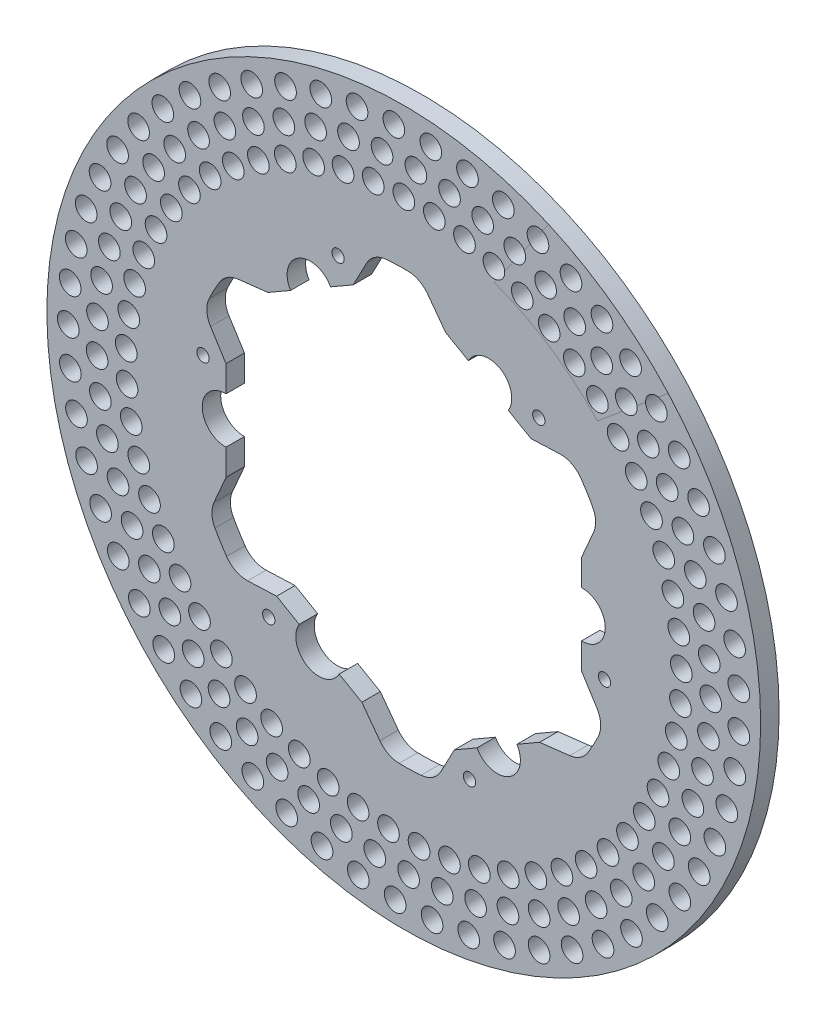
SolidWorks part; units mm, degrees
material "Gray Cast Iron"
ref_plane "Front Plane" through (0, 0, 0) normal (0, 0, 1) x (1, 0, 0)
ref_plane "Top Plane" through (0, 0, 0) normal (0, 1, 0) x (1, 0, 0)
ref_plane "Right Plane" through (0, 0, 0) normal (1, 0, 0) x (0, 0, -1)
sketch "Sketch1" plane through (0, 0, 0) normal (0, 0, 1) x (1, 0, 0)
  line L0 (-55.5625, 0) -> (-55.5625, -25.0191) construction
  line L1 (-45.8597, 11.4094) -> (-45.8597, 4.6599)
  line L2 (-45.8597, 11.4094) -> (-51.6236, 20.5474)
  line L3 (-45.8597, -13.9906) -> (-50.1583, -23.9026)
  line L4 (-45.8597, -7.2411) -> (-45.8597, -13.9906)
  line L5 (-13.049, 45.4204) -> (-8.0172, 54.981)
  line L6 (-13.049, 45.4204) -> (-18.8943, 42.0456)
  line L7 (-29.2008, 36.0951) -> (-35.0461, 32.7204)
  line L8 (-35.0461, 32.7204) -> (-45.7794, 31.4871)
  line L9 (32.8107, 34.011) -> (43.6064, 34.4336)
  line L10 (32.8107, 34.011) -> (26.9654, 37.3857)
  line L11 (16.6589, 43.3362) -> (10.8136, 46.711)
  line L12 (10.8136, 46.711) -> (4.3789, 55.3897)
  line L13 (45.8597, -11.4094) -> (51.6236, -20.5474)
  line L14 (45.8597, -11.4094) -> (45.8597, -4.6599)
  line L15 (45.8597, 7.2411) -> (45.8597, 13.9906)
  line L16 (45.8597, 13.9906) -> (50.1583, 23.9026)
  line L17 (13.049, -45.4204) -> (8.0172, -54.981)
  line L18 (13.049, -45.4204) -> (18.8943, -42.0456)
  line L19 (29.2008, -36.0951) -> (35.0461, -32.7204)
  line L20 (35.0461, -32.7204) -> (45.7794, -31.4871)
  line L21 (-32.8107, -34.011) -> (-43.6064, -34.4336)
  line L22 (-32.8107, -34.011) -> (-26.9654, -37.3857)
  line L23 (-16.6589, -43.3362) -> (-10.8136, -46.711)
  line L24 (-10.8136, -46.711) -> (-4.3789, -55.3897)
  circle A0 centre (0, 0) radius 92.075
  arc A1 (-45.7794, 31.4871) -> (-51.6236, 20.5474) centre (0, 0) ccw
  arc A3 (-45.8597, 4.6599) -> (-45.8597, -7.2411) centre (-46.0375, -1.2906) ccw
  arc A4 (-18.8943, 42.0456) -> (-29.2008, 36.0951) centre (-24.1364, 39.2243) ccw
  arc A5 (26.9654, 37.3857) -> (16.6589, 43.3362) centre (21.9011, 40.5149) ccw
  arc A6 (45.8597, -4.6599) -> (45.8597, 7.2411) centre (46.0375, 1.2906) ccw
  arc A7 (18.8943, -42.0456) -> (29.2008, -36.0951) centre (24.1364, -39.2243) ccw
  arc A8 (-26.9654, -37.3857) -> (-16.6589, -43.3362) centre (-21.9011, -40.5149) ccw
  arc A9 (4.3789, 55.3897) -> (-8.0172, 54.981) centre (0, 0) ccw
  arc A10 (50.1583, 23.9026) -> (43.6064, 34.4336) centre (0, 0) ccw
  arc A11 (45.7794, -31.4871) -> (51.6236, -20.5474) centre (0, 0) ccw
  arc A12 (-4.3789, -55.3897) -> (8.0172, -54.981) centre (0, 0) ccw
  arc A13 (-55.5625, 0) -> (-43.6064, -34.4336) centre (0, 0) ccw
  point P4 (0, 0)
  point P50 (0, 0)
  dimension "D1" = 184.15
  dimension "D2" = 111.125
  dimension "D3" = 11.9062
  dimension "D4" = 9.525
  dimension "D5" = 0.1778
  dimension "D6" = 25.4
  dimension "D7" = 44.45
  dimension "D9" = 47.2577
  dimension "D8" = 6
extrude "Boss-Extrude1" add sketch "Sketch1" along normal blind 4.7625
fillet "Fillet1" radius 6.35 12 edges at (8.0172, -54.981, 2.3813) (45.7794, -31.4871, 2.3813) (-4.3789, -55.3897, 2.3813) (-43.6064, -34.4336, 2.3813) (51.6236, -20.5474, 2.3813) (50.1583, 23.9026, 2.3813) (43.6064, 34.4336, 2.3813) (4.3789, 55.3897, 2.3813) (-50.1583, -23.9026, 2.3813) (-51.6236, 20.5474, 2.3813) (-8.0172, 54.981, 2.3813) (-45.7794, 31.4871, 2.3813)
sketch "Sketch4" plane through (0, 0, 4.7625) normal (0, 0, 1) x (1, 0, 0)
  circle A0 centre (-16.953, 50.0113) radius 1.5875
  arc A1 (-18.8943, 42.0456) -> (-29.2008, 36.0951) centre (-24.1364, 39.2243) ccw construction
  circle A3 centre (34.8346, 39.6874) radius 1.5875
  circle A4 centre (51.7876, -10.3239) radius 1.5875
  circle A5 centre (16.953, -50.0113) radius 1.5875
  circle A6 centre (-34.8346, -39.6874) radius 1.5875
  circle A7 centre (-51.7876, 10.3239) radius 1.5875
  point P6 (-27.113, 44.3799)
  point P23 (0, 0)
  dimension "D1" = 52.8066
  dimension "D2" = 3.175
  dimension "D3" = 10.16
  dimension "D4" = 6
extrude "Cut-Extrude1" cut sketch "Sketch4" against normal through all
sketch "Sketch5" plane through (0, 0, 4.7625) normal (0, 0, 1) x (1, 0, 0)
  line L0 (-0.9624, 90.7456) -> (18.947, 86.7084) construction
  line L1 (2.55, 93.4319) -> (16.7734, 90.5477) construction
  circle A0 centre (0, 0) radius 68.58 construction
  circle A1 centre (0, 71.628) radius 2.794
  circle A2 centre (3.1223, 79.1324) radius 2.794
  circle A3 centre (6.9872, 86.2827) radius 2.794
  circle A8 centre (0, 0) radius 92.075 construction
  dimension "D1" = 137.16
  dimension "D2" = 71.628
  dimension "D3" = 5.588
  dimension "D4" = 8.128
  dimension "D5" = 8.128
extrude "Cut-Extrude2" cut sketch "Sketch5" against normal through all
pattern_circular "CirPattern1" count 57 over 360 about axis through (0, 0, 0) along (0, 0, 1) of "Cut-Extrude2"
sketch "Sketch6" plane through (0, 0, 4.7625) normal (0, 0, 1) x (1, 0, 0)
  line L0 (0, 0) -> (0, 110.5188) construction
  line L1 (0, 0) -> (38.9978, 107.1456) construction
  line L4 (23.3472, 64.1458) -> (37.3582, 84.1556)
  line L5 (49.9701, 46.5054) -> (68.2294, 61.8268)
  arc A2 (68.2294, 61.8268) -> (37.3582, 84.1556) centre (0, 0) ccw
  arc A3 (49.9701, 46.5054) -> (23.3472, 64.1458) centre (0, 0) ccw
  dimension "D2" = 15
  dimension "D3" = 184.15
  dimension "D6" = 136.525
  dimension "D1" = 20
  dimension "D4" = 15
  dimension "D5" = 38.1
split line "Split Line1"
equation "\"holenumber\"=57.000000"
equation "\"D1@CirPattern1\"=\"holenumber\""
